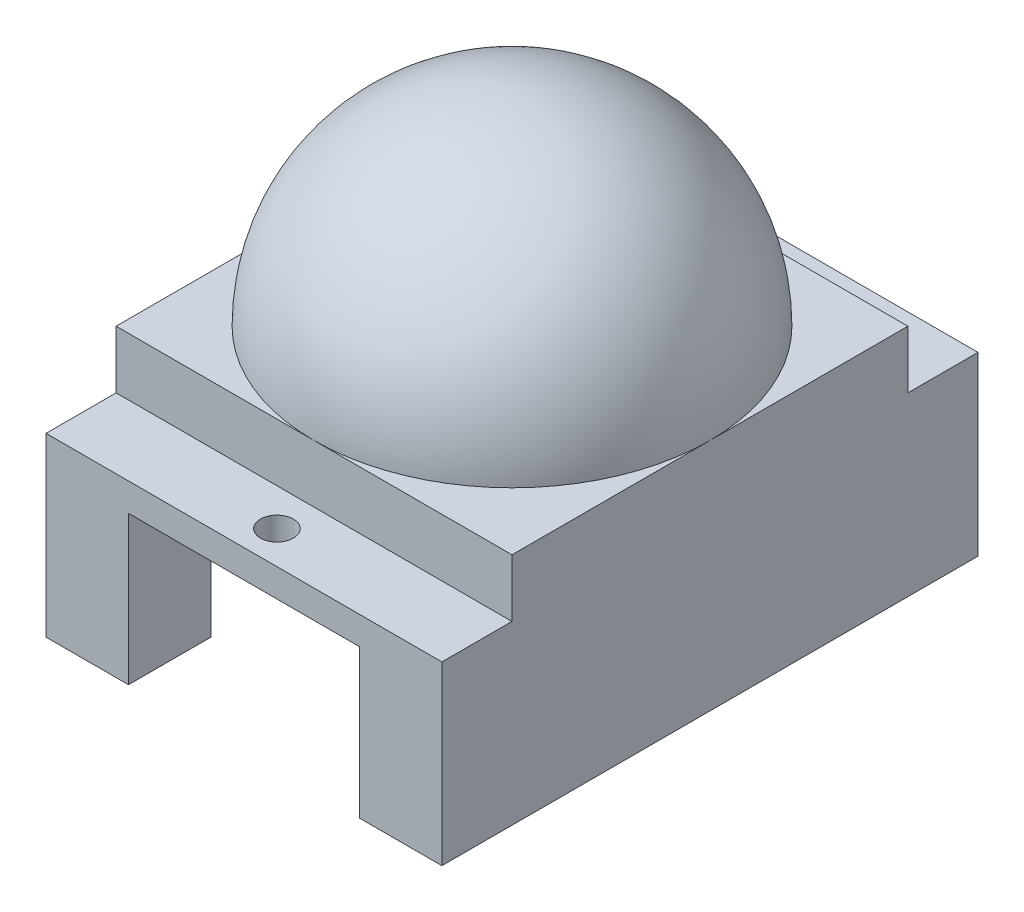
SolidWorks part; units mm, degrees
ref_plane "Front Plane" through (0, 0, 0) normal (0, 0, 1) x (1, 0, 0)
ref_plane "Top Plane" through (0, 0, 0) normal (0, 1, 0) x (1, 0, 0)
ref_plane "Right Plane" through (0, 0, 0) normal (1, 0, 0) x (0, 0, -1)
sketch "Sketch1" plane through (0, 0, 0) normal (0, 1, 0) x (1, 0, 0)
  line L0 (0, 16.25) -> (0, -16.25) construction
  line L1 (-12, 16.25) -> (12, 16.25)
  line L2 (-12, 16.25) -> (-12, -16.25)
  line L3 (-12, -16.25) -> (12, -16.25)
  line L4 (12, 16.25) -> (12, -16.25)
  line L5 (-12, 16.25) -> (12, -16.25) construction
  line L6 (-12, -16.25) -> (12, 16.25) construction
  circle A0 centre (0, 14.25) radius 1
  circle A1 centre (0, -14.25) radius 1
  point P0 (0, 0)
  dimension "D3" = 2
  dimension "D1" = 24
  dimension "D2" = 32.5
  dimension "D4" = 2
  dimension "D5" = 2
extrude "Boss-Extrude1" add sketch "Sketch1" along normal blind 1.7
sketch "Sketch2" plane through (0, 1.7, 0) normal (0, 1, 0) x (1, 0, 0)
  line L0 (12, -16.25) -> (12, 16.25) construction
  line L1 (-12, 12) -> (12, 12)
  line L2 (-12, 12) -> (-12, -12)
  line L3 (-12, -12) -> (12, -12)
  line L4 (12, 12) -> (12, -12)
  line L5 (-12, 12) -> (12, -12) construction
  line L6 (-12, -12) -> (12, 12) construction
  point P0 (0, 0)
  dimension "D1" = 24
extrude "Boss-Extrude2" add sketch "Sketch2" along normal blind 3.5
sketch "Sketch3" plane through (0, 0, 0) normal (0, 0, 1) x (1, 0, 0)
  line L0 (0, 0) -> (0, 17.2) construction
  line L1 (-12, 5.2) -> (12, 5.2) construction
  line L2 (0, 5.2) -> (12, 5.2) construction
  line L4 (0, 17.2) -> (0, 5.2)
  line L5 (0, 5.2) -> (12, 5.2)
  arc A0 (12, 5.2) -> (0, 17.2) centre (0, 5.2) ccw
  dimension "D1" = 12
revolve "Revolve1" add sketch "Sketch3" angle 360 about L4
sketch "Sketch4" plane through (0, 0, 0) normal (0, -1, 0) x (1, 0, 0)
  line L0 (7, -4.0625) -> (12, 16.25) construction
  line L1 (7, 16.25) -> (12, 16.25)
  line L2 (4, -12.75) -> (4, -16.25)
  line L3 (4, -16.25) -> (12, -16.25)
  line L4 (12, 16.25) -> (12, -16.25)
  line L5 (7, 4.0625) -> (12, -16.25) construction
  line L6 (4, -16.25) -> (4.8615, -12.75) construction
  line L7 (-12, -16.25) -> (-12, 16.25) construction
  line L8 (-12, 16.25) -> (-7, 16.25)
  line L9 (4, -12.75) -> (7, -12.75)
  line L10 (7, 16.25) -> (7, -12.75)
  line L11 (-12, 16.25) -> (-12, 11.25)
  line L12 (-12, 11.25) -> (-7, 11.25)
  line L13 (-7, 16.25) -> (-7, 11.25)
  line L14 (-12, -16.25) -> (-7, -16.25)
  line L15 (-12, -16.25) -> (-12, -11.25)
  line L16 (-12, -11.25) -> (-7, -11.25)
  line L17 (-7, -16.25) -> (-7, -11.25)
  line L18 (-12, 4) -> (-7, 4)
  line L19 (-12, 4) -> (-12, -4)
  line L20 (-12, -4) -> (-7, -4)
  line L21 (-7, 4) -> (-7, -4)
  point P0 (8, 0)
  point P27 (-7, 0)
  dimension "D1" = 8
  dimension "D2" = 3
  dimension "D3" = 3.5
  dimension "D4" = 8
  dimension "D5" = 5
extrude "Boss-Extrude3" add sketch "Sketch4" along normal blind 9
